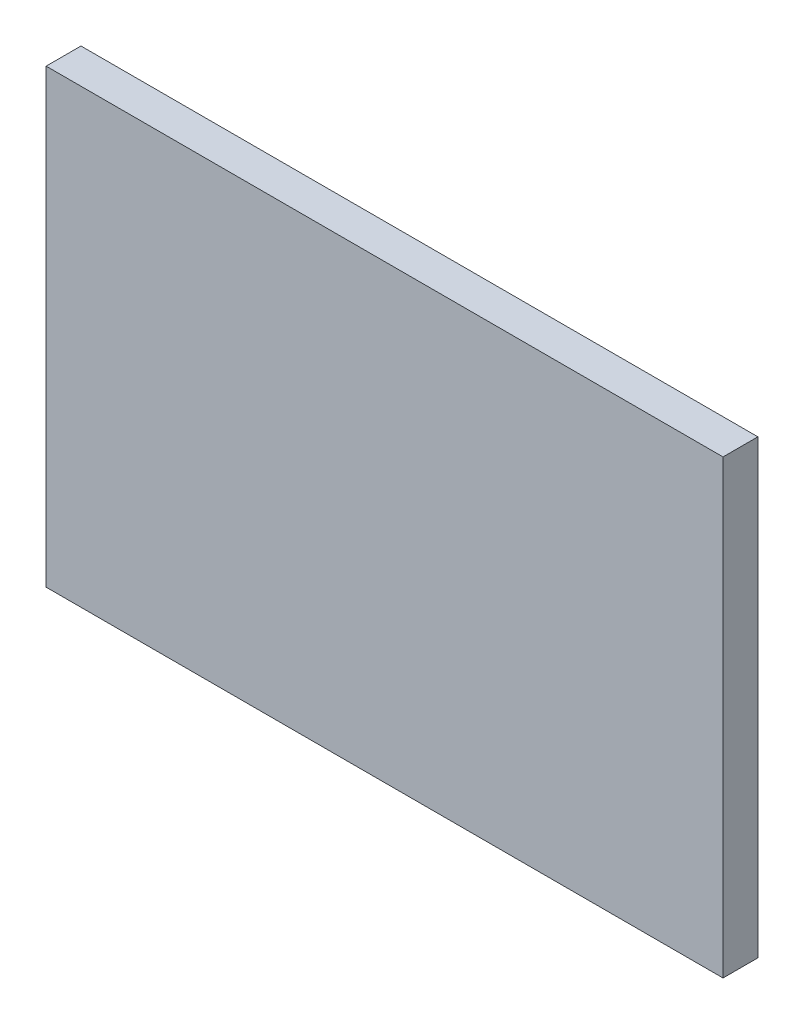
SolidWorks part; units mm, degrees
ref_plane "Спереди" through (0, 0, 0) normal (0, 0, 1) x (1, 0, 0)
ref_plane "Сверху" through (0, 0, 0) normal (0, 1, 0) x (1, 0, 0)
ref_plane "Справа" through (0, 0, 0) normal (1, 0, 0) x (0, 0, -1)
sketch "Эскиз1" plane through (0, 0, 0) normal (0, 0, 1) x (1, 0, 0)
  line L1 (-1942.5, 1295) -> (1942.5, 1295)
  line L2 (-1942.5, 1295) -> (-1942.5, -1295)
  line L3 (-1942.5, -1295) -> (1942.5, -1295)
  line L4 (1942.5, 1295) -> (1942.5, -1295)
  line L5 (-1942.5, 1295) -> (1942.5, -1295) construction
  line L6 (-1942.5, -1295) -> (1942.5, 1295) construction
  point P1 (0, 0)
extrude "Бобышка-Вытянуть1" add sketch "Эскиз1" along normal blind 200
